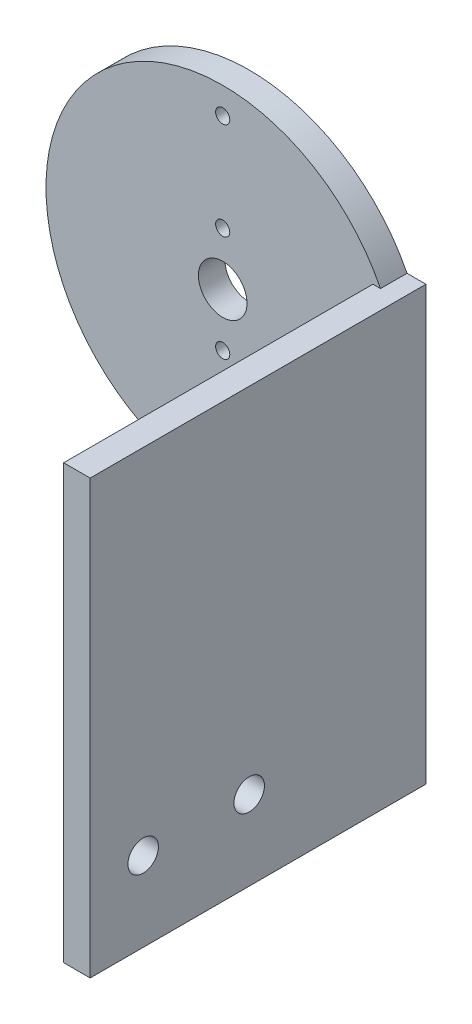
SolidWorks part; units mm, degrees
ref_plane "Front Plane" through (0, 0, 0) normal (0, 0, 1) x (1, 0, 0)
ref_plane "Top Plane" through (0, 0, 0) normal (0, 1, 0) x (1, 0, 0)
ref_plane "Right Plane" through (0, 0, 0) normal (1, 0, 0) x (0, 0, -1)
sketch "Sketch1" plane through (0, 0, 0) normal (0, 0, 1) x (1, 0, 0)
  circle A0 centre (0, 0) radius 20
extrude "Boss-Extrude1" add sketch "Sketch1" along normal blind 3 from offset 26
sketch "Sketch2" plane through (0, 0, 0) normal (0, 0, 1) x (1, 0, 0)
  line L0 (0, -40) -> (20, -40)
  line L1 (20, -40) -> (20, 9)
  line L2 (20, 9) -> (0, 9)
  line L3 (0, 9) -> (0, -40)
extrude "Boss-Extrude2" add sketch "Sketch2" along normal blind 3 from offset 26
sketch "Sketch3" plane through (0, 0, 0) normal (0, 0, 1) x (1, 0, 0)
  line L0 (17, -40) -> (20, -40)
  line L1 (20, -40) -> (20, 9)
  line L2 (20, 9) -> (17, 9)
  line L3 (17, 9) -> (17, -40)
extrude "Boss-Extrude3" add sketch "Sketch3" along normal blind 38 from offset 26
sketch "Sketch4" plane through (0, 0, 0) normal (0, 0, 1) x (1, 0, 0)
  circle A0 centre (0, 0) radius 2.75
  circle A1 centre (0, 6) radius 0.8
  circle A2 centre (0, -6) radius 0.8
  circle A3 centre (0, 17) radius 0.8
  circle A4 centre (0, -17) radius 0.8
extrude "Cut-Extrude1" cut sketch "Sketch4" against normal through all and the other way through all
sketch "Sketch5" plane through (0, 0, 0) normal (1, 0, 0) x (0, 0, -1)
  circle A0 centre (-6, -31) radius 1.725
  circle A1 centre (6, -31) radius 1.725
extrude "Cut-Extrude2" cut sketch "Sketch5" against normal through all and the other way through all
